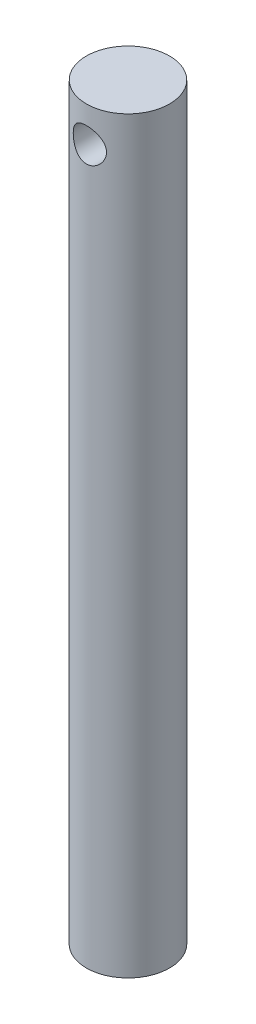
SolidWorks part; units mm, degrees
ref_plane "Front Plane" through (0, 0, 0) normal (0, 0, 1) x (1, 0, 0)
ref_plane "Top Plane" through (0, 0, 0) normal (0, 1, 0) x (1, 0, 0)
ref_plane "Right Plane" through (0, 0, 0) normal (1, 0, 0) x (0, 0, -1)
sketch "Эскиз1" plane through (0, 0, 0) normal (0, 1, 0) x (1, 0, 0)
  circle A0 centre (0, 0) radius 10
extrude "Вытянуть1" add sketch "Эскиз1" along normal blind 180 from offset 20 offset against normal yes
sketch "Эскиз2" plane through (0, 0, 0) normal (0, 0, 1) x (1, 0, 0)
  circle A0 centre (0, 151.5) radius 4
extrude "Вытянуть2" cut sketch "Эскиз2" against normal mid plane 50
